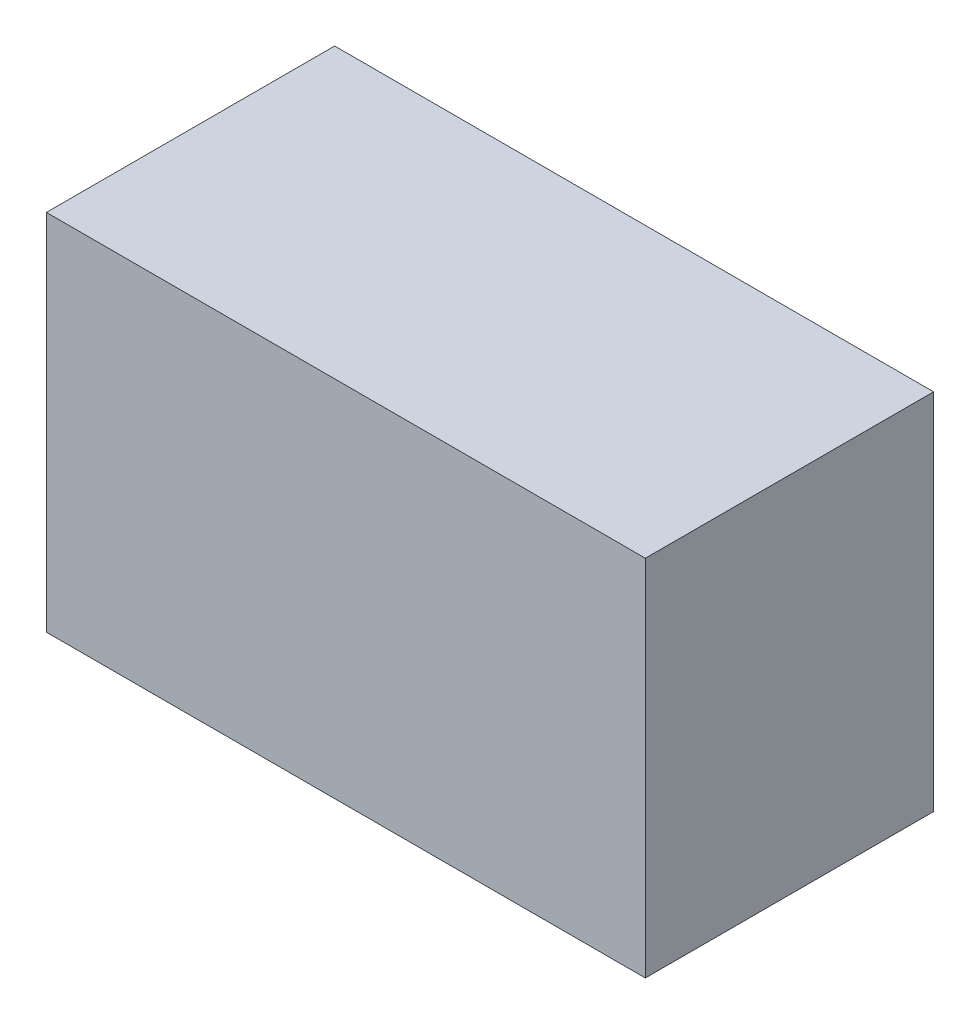
SolidWorks part; units mm, degrees
ref_plane "Front Plane" through (0, 0, 0) normal (0, 0, 1) x (1, 0, 0)
ref_plane "Top Plane" through (0, 0, 0) normal (0, 1, 0) x (1, 0, 0)
ref_plane "Right Plane" through (0, 0, 0) normal (1, 0, 0) x (0, 0, -1)
sketch "Sketch1" plane through (0, 0, 0) normal (0, 0, 1) x (1, 0, 0)
  circle A0 centre (0.0577, -0.6298) radius 13.0443
extrude "Boss-Extrude1" add sketch "Sketch1" along normal blind 2
sketch "Sketch2" plane through (0, 0, 2) normal (0, 0, 1) x (1, 0, 0)
  line L1 (20.7797, -12.6121) -> (-20.7797, -12.6121)
  line L2 (20.7797, -12.6121) -> (20.7797, 12.6121)
  line L3 (20.7797, 12.6121) -> (-20.7797, 12.6121)
  line L4 (-20.7797, -12.6121) -> (-20.7797, 12.6121)
  line L5 (20.7797, -12.6121) -> (-20.7797, 12.6121) construction
  line L6 (20.7797, 12.6121) -> (-20.7797, -12.6121) construction
  point P0 (0, 0)
extrude "Boss-Extrude2" add sketch "Sketch2" along normal mid plane 20 separate body
ref_plane "Plane2" through (0, 0, 2) normal (0, 0, -1) x (-1, 0, 0)
ref_plane "Plane3" through (0, 0, 0) normal (-1, 0, 0) x (0, 0, 1)
ref_plane "Plane4" through (0, 0, 0) normal (0, 1, 0) x (1, 0, 0)
